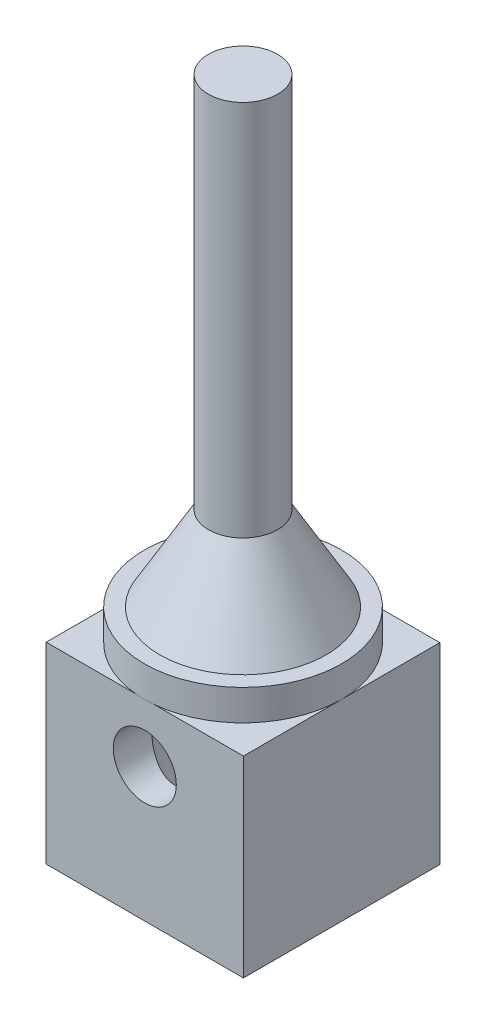
SolidWorks part; units mm, degrees
ref_plane "Front Plane" through (0, 0, 0) normal (0, 0, 1) x (1, 0, 0)
ref_plane "Top Plane" through (0, 0, 0) normal (0, 1, 0) x (1, 0, 0)
ref_plane "Right Plane" through (0, 0, 0) normal (1, 0, 0) x (0, 0, -1)
sketch "Sketch4" plane through (0, 0, 0) normal (0, 1, 0) x (1, 0, 0)
  line L0 (4.4831, 0) -> (4.4831, 2.6276) construction
  line L1 (-6.5151, -6.4884) -> (6.5151, -6.4884)
  line L2 (-6.5151, -6.4884) -> (-6.5151, 6.4884)
  line L3 (-6.5151, 6.4884) -> (6.5151, 6.4884)
  line L4 (6.5151, -6.4884) -> (6.5151, 6.4884)
  line L5 (-6.5151, -6.4884) -> (6.5151, 6.4884) construction
  line L6 (-6.5151, 6.4884) -> (6.5151, -6.4884) construction
  circle A0 centre (0, 0) radius 4.4831
  dimension "D1" = 8.9662
  dimension "D2" = 2.032
extrude "Boss-Extrude3" add sketch "Sketch4" along normal blind 12.7
sketch "Sketch5" plane through (0, 0, 6.4884) normal (0, 0, 1) x (1, 0, 0)
  line L0 (0, 12.7) -> (0, 0) construction
  line L1 (-6.5151, 12.7) -> (6.5151, 12.7) construction
  line L2 (0, 10.922) -> (-1.8492, 10.922) construction
  circle A0 centre (0, 8.8392) radius 2.0828
  dimension "D1" = 4.1656
  dimension "D2" = 1.778
extrude "Cut-Extrude4" cut sketch "Sketch5" against normal blind 15.24
sketch "Sketch6" plane through (0, 12.7, 0) normal (0, 1, 0) x (1, 0, 0)
  circle A0 centre (0, 0) radius 6.5151
  circle A1 centre (0, 0) radius 4.4831 construction
  dimension "D1" = 2.032
extrude "Boss-Extrude4" add sketch "Sketch6" along normal blind 2.032
sketch "Sketch7" plane through (0, 14.732, 0) normal (0, 1, 0) x (1, 0, 0)
  circle A0 centre (0, 0) radius 2.286
  dimension "D1" = 4.572
extrude "Boss-Extrude6" add sketch "Sketch7" along normal blind 30.48
chamfer "Chamfer1" distance 3.2092 angle 60 1 edges at (0, 14.732, 2.286)
